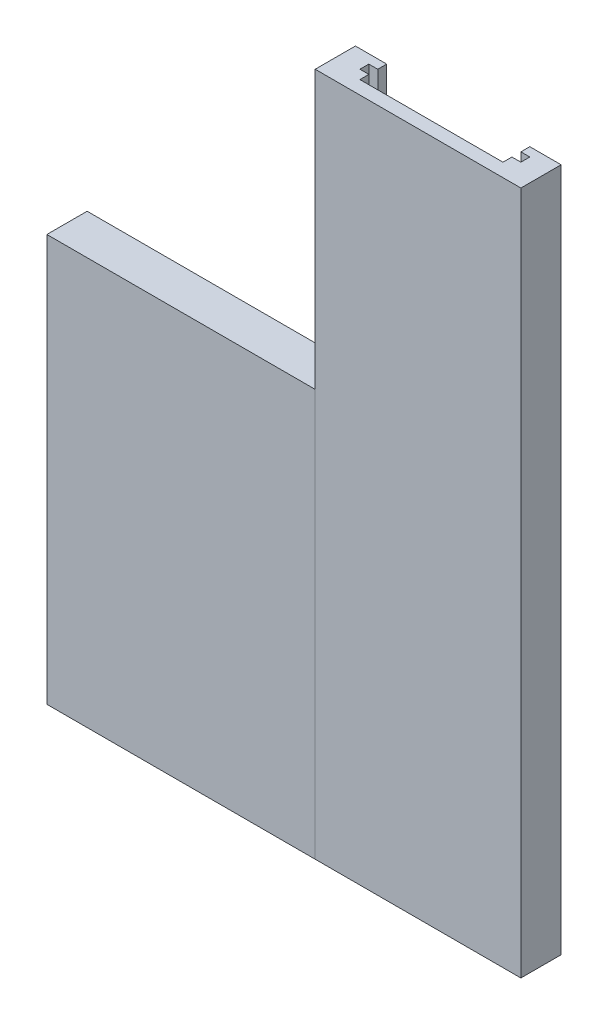
SolidWorks part; units mm, degrees
ref_plane "Přední rovina" through (0, 0, 0) normal (0, 0, 1) x (1, 0, 0)
ref_plane "Horní rovina" through (0, 0, 0) normal (0, 1, 0) x (1, 0, 0)
ref_plane "Pravá rovina" through (0, 0, 0) normal (1, 0, 0) x (0, 0, -1)
sketch "Skica1" plane through (0, 0, 0) normal (0, 0, 1) x (1, 0, 0)
  line L1 (43, -3) -> (40, -3)
  line L2 (43, -3) -> (43, 150)
  line L4 (40, 0) -> (40, 150)
  line L5 (43, -3) -> (-63, -3) construction
  line L6 (-3, -3) -> (0, -3)
  line L7 (-3, -3) -> (-3, 150)
  line L9 (0, 0) -> (0, 150)
  line L10 (0, 150) -> (0, 115) construction
  line L11 (-3, 112) -> (-3, 153) construction
  line L12 (40, 115) -> (40, 150) construction
  line L13 (0, 150) -> (-3, 150)
  line L18 (0, -3) -> (40, -3)
  line L20 (0, 0) -> (40, 0)
  line L22 (40, 150) -> (43, 150)
  line L23 (40, 150) -> (43, 150) construction
extrude "Přidat vysunutím1" add sketch "Skica1" along normal blind 6
sketch "Skica2" plane through (0, 0, 6) normal (0, 0, 1) x (1, 0, 0)
  line L11 (-3, -3) -> (43, -3)
  line L12 (-3, -3) -> (-3, 150)
  line L13 (-3, 150) -> (43, 150)
  line L14 (43, -3) -> (43, 150)
extrude "Přidat vysunutím2" add sketch "Skica2" along normal blind 3
sketch "Skica3" plane through (0, -3, 0) normal (0, -1, 0) x (1, 0, 0)
  line L1 (3, 3) -> (0, 3) construction
  line L2 (0, 0) -> (4, 0)
  line L3 (0, 0) -> (0, 6)
  line L4 (0, 6) -> (4, 6)
  line L5 (4, 0) -> (4, 2)
  line L6 (40, 0) -> (36, 0)
  line L7 (40, 0) -> (40, 6)
  line L8 (40, 6) -> (36, 6)
  line L9 (36, 0) -> (36, 2)
  line L10 (37, 3) -> (40, 3) construction
  line L11 (2, 2) -> (4, 2)
  line L12 (2, 2) -> (2, 4)
  line L13 (2, 4) -> (4, 4)
  line L15 (2, 2) -> (4, 4) construction
  line L16 (2, 4) -> (4, 2) construction
  line L17 (36, 4) -> (36, 6)
  line L18 (38, 2) -> (36, 2)
  line L19 (38, 2) -> (38, 4)
  line L20 (38, 4) -> (36, 4)
  line L22 (38, 2) -> (36, 4) construction
  line L23 (38, 4) -> (36, 2) construction
  line L24 (4, 4) -> (4, 6)
  line L25 (-3, 0) -> (43, 0) construction
  line L26 (43, 9) -> (43, 0) construction
  point P15 (3, 3)
  point P22 (37, 3)
  dimension "D1" = 4
  dimension "D2" = 4
  dimension "D3" = 2
  dimension "D4" = 2
  dimension "D5" = 2
  dimension "D6" = 2
  dimension "D7" = 2
  dimension "D8" = 2
  dimension "D9" = 2
  dimension "D10" = 2
  dimension "D11" = 32
  dimension "D12" = 36
sketch "Skica5" plane through (0, 0, 9) normal (0, 0, 1) x (1, 0, 0)
  line L1 (-3, 88) -> (-63, 88) construction
  line L2 (-63, -3) -> (-3, -3)
  line L3 (-63, -3) -> (-63, 88)
  line L4 (-63, 88) -> (-3, 88)
  line L5 (-3, -3) -> (-3, 88)
  line L6 (-63, 88) -> (-63, -3) construction
  line L8 (43, -3) -> (-63, -3) construction
  point P2 (-63, -3)
extrude "Přidat vysunutím4" add sketch "Skica5" against normal blind 6 separate body
ref_plane "Rovina1" through (-63, -3, 3) normal (1, 0, 0) x (0, 0, -1)
sketch "Skica7" plane through (0, 0, 3) normal (0, 0, -1) x (-1, 0, 0)
  line L0 (60, 0) -> (60, 85)
  line L1 (63, -3) -> (3, -3)
  line L2 (63, -3) -> (63, 88)
  line L3 (63, 88) -> (3, 88)
  line L4 (3, -3) -> (3, 88)
  line L5 (60, 85) -> (6, 85)
  line L6 (6, 0) -> (6, 85)
  line L7 (60, 0) -> (6, 0)
  dimension "D1" = 3
extrude "Přidat vysunutím5" add sketch "Skica7" along normal through all
extrude "Přidat vysunutím6" add sketch "Skica3" against normal through all
